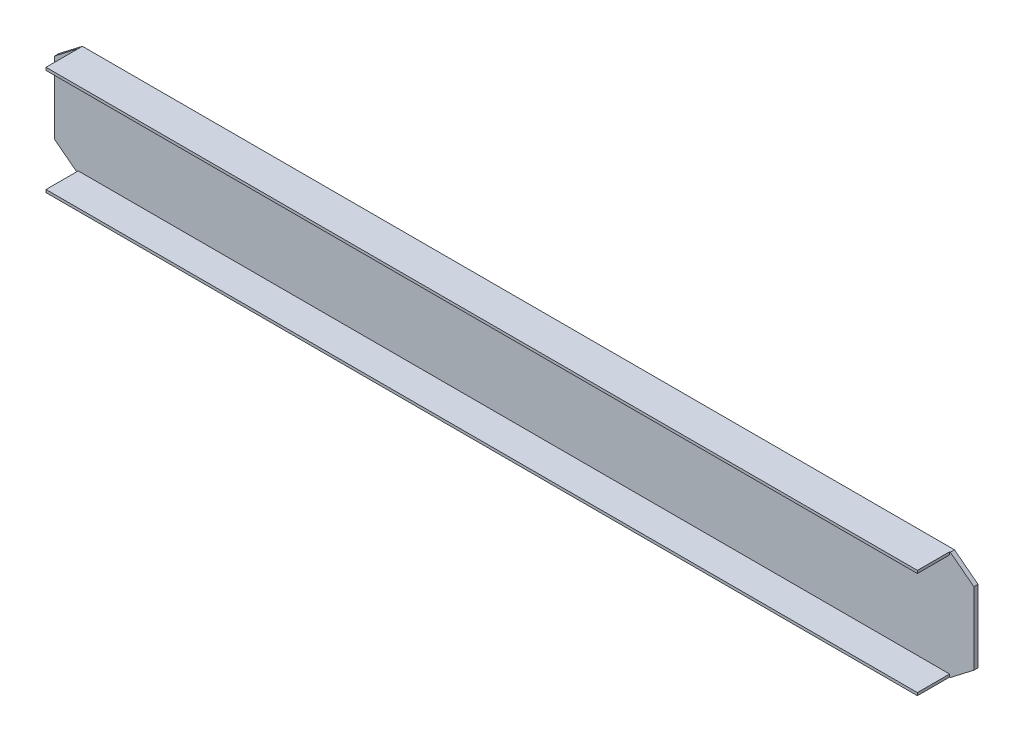
SolidWorks part; units mm, degrees
ref_plane "前视" through (0, 0, 0) normal (0, 0, 1) x (1, 0, 0)
ref_plane "上视" through (0, 0, 0) normal (0, 1, 0) x (1, 0, 0)
ref_plane "右视" through (0, 0, 0) normal (1, 0, 0) x (0, 0, -1)
sketch "草图1" plane through (0, 0, 0) normal (0, 0, 1) x (1, 0, 0)
  line L0 (0, -30.9807) -> (0, 402.9291) construction
  line L1 (-1205, 0) -> (1205, 0)
  line L2 (-1270, 50) -> (-1270, 250)
  line L3 (-1205, 300) -> (1205, 300)
  line L4 (-1270, 50) -> (-1205, 0)
  line L5 (-1270, 250) -> (-1205, 300)
  line L6 (-1329.5124, 150) -> (23.7415, 150) construction
  line L7 (-1307.9834, 230) -> (-31.6189, 230) construction
  line L8 (-1220, -101.4655) -> (-1220, 369.0978) construction
  line L9 (1270, 250) -> (1205, 300)
  line L10 (-1140, 369.0978) -> (-1140, -101.4655) construction
  line L11 (1270, 50) -> (1205, 0)
  line L12 (-1060, -101.4655) -> (-1060, 369.0978) construction
  line L13 (1270, 50) -> (1270, 250)
  line L14 (-980, 369.0978) -> (-980, -101.4655) construction
  circle A0 centre (-1220, 230) radius 13
  circle A1 centre (-1220, 150) radius 13
  circle A2 centre (-1140, 230) radius 13
  circle A3 centre (-1140, 150) radius 13
  circle A4 centre (-1060, 230) radius 13
  circle A5 centre (-1060, 150) radius 13
  circle A6 centre (-980, 150) radius 13
  circle A7 centre (-1060, 70) radius 13
  circle A8 centre (-1140, 70) radius 13
  circle A9 centre (-1220, 70) radius 13
  circle A10 centre (1220, 70) radius 13
  circle A11 centre (1140, 70) radius 13
  circle A12 centre (1060, 70) radius 13
  circle A13 centre (980, 150) radius 13
  circle A14 centre (1060, 150) radius 13
  circle A15 centre (1060, 230) radius 13
  circle A16 centre (1140, 150) radius 13
  circle A17 centre (1140, 230) radius 13
  circle A18 centre (1220, 150) radius 13
  circle A19 centre (1220, 230) radius 13
  circle A20 centre (-980, 70) radius 13
  circle A21 centre (-980, 230) radius 13
  circle A22 centre (980, 70) radius 13
  circle A23 centre (980, 230) radius 13
  point P8 (0, 300)
  point P65 (0, 0)
  dimension "D13" = 26
  dimension "D14" = 26
  dimension "D1" = 1205
  dimension "D2" = 300
  dimension "D3" = 65
  dimension "D4" = 65
  dimension "D5" = 50
  dimension "D6" = 50
  dimension "D7" = 70
  dimension "D8" = 80
  dimension "D9" = 50
  dimension "D10" = 80
  dimension "D11" = 80
  dimension "D12" = 80
  dimension "D15" = 70
  dimension "D16" = 70
extrude "基体-拉伸" add sketch "草图1" against normal blind 11.5
sketch "草图2" plane through (0, 0, 0) normal (0, 0, 1) x (1, 0, 0)
  line L0 (-1399.9508, 150) -> (-832.4876, 150) construction
  line L1 (-1205, 300) -> (1203.049, 300)
  line L2 (-1205, 300) -> (-1205, 292.5)
  line L3 (-1205, 292.5) -> (1203.049, 292.5)
  line L4 (1203.049, 300) -> (1203.049, 292.5)
  line L5 (-1205, 0) -> (1205, 0) construction
  line L6 (1203.049, 0) -> (1203.049, 7.5)
  line L7 (-1205, 7.5) -> (1203.049, 7.5)
  line L8 (-1205, 0) -> (-1205, 7.5)
  line L9 (-1205, 0) -> (1203.049, 0)
  dimension "D1" = 7.5
extrude "凸台-拉伸1" add sketch "草图2" along normal blind 89
sketch "草图3" plane through (0, 0, -11.5) normal (0, 0, -1) x (-1, 0, 0)
  line L0 (0, -46.5184) -> (0, 412.0245) construction
  line L1 (-180, 412.0245) -> (-180, -46.5184) construction
  line L2 (-580, 412.0245) -> (-580, -73.5011) construction
  line L3 (-1205, 300) -> (1205, 300) construction
  line L4 (-620, 270) -> (-540, 270)
  line L5 (-620, 270) -> (-620, 30)
  line L6 (-620, 30) -> (-540, 30)
  line L7 (-540, 270) -> (-540, 30)
  line L8 (-220, 270) -> (-140, 270)
  line L9 (-220, 270) -> (-220, 30)
  line L10 (-220, 30) -> (-140, 30)
  line L11 (-140, 270) -> (-140, 30)
  line L12 (140, 270) -> (140, 30)
  line L13 (220, 30) -> (140, 30)
  line L14 (220, 270) -> (220, 30)
  line L15 (220, 270) -> (140, 270)
  line L16 (540, 270) -> (540, 30)
  line L17 (620, 30) -> (540, 30)
  line L18 (620, 270) -> (620, 30)
  line L19 (620, 270) -> (540, 270)
  dimension "D1" = 180
  dimension "D2" = 400
  dimension "D3" = 240
  dimension "D4" = 30
  dimension "D5" = 80
  dimension "D6" = 80
extrude "凸台-拉伸2" add sketch "草图3" along normal blind 16
sketch "草图4" plane through (0, 0, 0) normal (0, 0, 1) x (1, 0, 0)
  line L0 (0, -259.4133) -> (0, 624.9194) construction
  line L1 (-180, -162.9649) -> (-180, 487.5033) construction
  line L2 (1203.049, 300) -> (-1205, 300) construction
  line L3 (-580, 487.5033) -> (-580, -162.9649) construction
  line L4 (-781.6864, 230) -> (-55.0372, 230) construction
  line L6 (-55.0372, 150) -> (-781.6864, 150) construction
  line L8 (-781.6864, 70) -> (-55.0372, 70) construction
  circle A0 centre (-580, 230) radius 13
  circle A1 centre (-580, 150) radius 13
  circle A2 centre (-180, 230) radius 13
  circle A3 centre (-180, 150) radius 13
  circle A4 centre (-180, 70) radius 13
  circle A5 centre (-580, 70) radius 13
  circle A6 centre (580, 70) radius 13
  circle A7 centre (180, 70) radius 13
  circle A8 centre (180, 150) radius 13
  circle A9 centre (180, 230) radius 13
  circle A10 centre (580, 150) radius 13
  circle A11 centre (580, 230) radius 13
  dimension "D6" = 26
  dimension "D1" = 180
  dimension "D2" = 400
  dimension "D3" = 70
  dimension "D4" = 80
  dimension "D5" = 80
extrude "切除-拉伸1" cut sketch "草图4" against normal through all
sketch "草图5" plane through (0, 0, 0) normal (0, 0, 1) x (1, 0, 0)
  line L0 (-1270, 250) -> (-1270, 50)
  line L1 (-1270, 50) -> (-1205, 0)
  line L2 (-1205, 0) -> (1205, 0)
  line L3 (1205, 0) -> (1270, 50)
  line L4 (1270, 50) -> (1270, 250)
  line L5 (1270, 250) -> (1205, 300)
  line L6 (1205, 300) -> (-1205, 300)
  line L7 (-1205, 300) -> (-1270, 250)
extrude "凸台-拉伸3" add sketch "草图5" against normal blind 11.5
sketch "草图6" plane through (0, 0, -11.5) normal (0, 0, -1) x (-1, 0, 0)
  line L1 (-620, 270) -> (-540, 270)
  line L2 (-620, 270) -> (-620, 30)
  line L3 (-620, 30) -> (-540, 30)
  line L4 (-540, 270) -> (-540, 30)
  line L5 (-220, 270) -> (-140, 270)
  line L6 (-220, 270) -> (-220, 30)
  line L7 (-220, 30) -> (-140, 30)
  line L8 (-140, 270) -> (-140, 30)
  line L9 (140, 270) -> (220, 270)
  line L10 (140, 270) -> (140, 30)
  line L11 (140, 30) -> (220, 30)
  line L12 (220, 270) -> (220, 30)
  line L13 (540, 270) -> (620, 270)
  line L14 (540, 270) -> (540, 30)
  line L15 (540, 30) -> (620, 30)
  line L16 (620, 270) -> (620, 30)
extrude "凸台-拉伸4" add sketch "草图6" along normal blind 16
